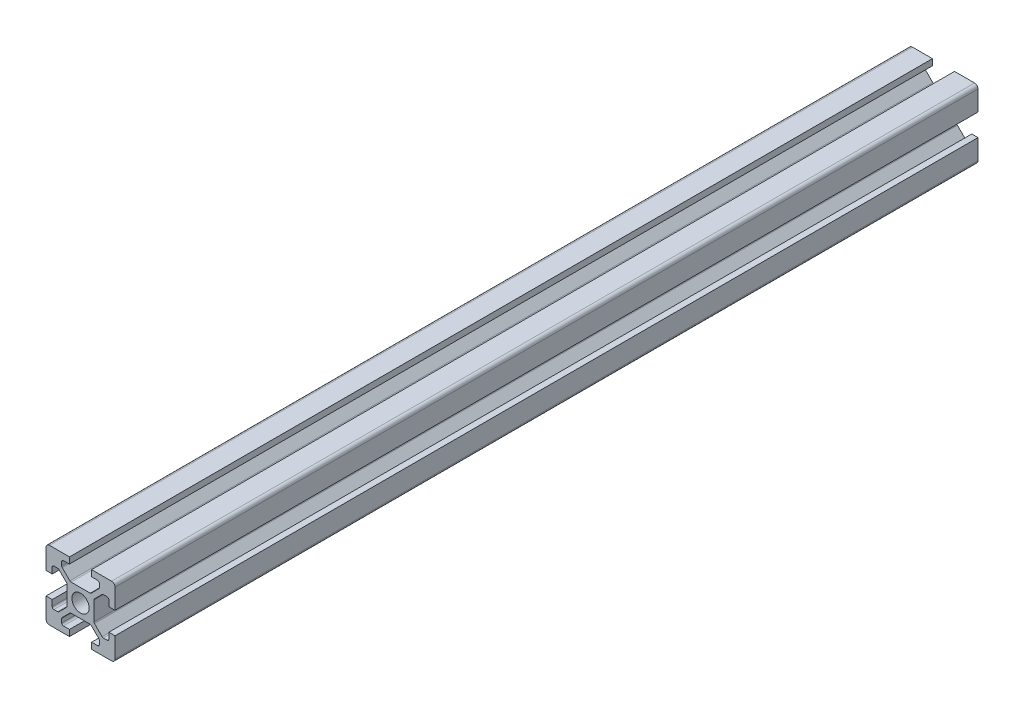
SolidWorks part; units mm, degrees
material "1060 Alloy"
ref_plane "Front Plane" through (0, 0, 0) normal (0, 0, 1) x (1, 0, 0)
ref_plane "Top Plane" through (0, 0, 0) normal (0, 1, 0) x (1, 0, 0)
ref_plane "Right Plane" through (0, 0, 0) normal (1, 0, 0) x (0, 0, -1)
sketch "Sketch1" plane through (0, 0, 0) normal (0, 0, 1) x (1, 0, 0)
  line L0 (20, 0) -> (-8.059, 28.059) construction
  line L1 (0, 0) -> (6.8, 0)
  line L2 (0, 0) -> (0, 6.8)
  line L3 (0, 20) -> (6.8, 20)
  line L4 (20, 0) -> (20, 6.8)
  line L5 (6.8, 20) -> (6.8, 18.2)
  line L6 (20, 20) -> (8.2322, 8.2322) construction
  line L7 (12.95, 6.1) -> (7.05, 6.1)
  line L8 (13.9, 7.05) -> (13.9, 12.95)
  line L9 (12.95, 13.9) -> (7.05, 13.9)
  line L10 (6.1, 7.05) -> (6.1, 12.95)
  line L11 (13.9, 6.1) -> (6.1, 13.9) construction
  line L12 (13.9, 13.9) -> (6.1, 6.1) construction
  line L13 (4.55, 16.4) -> (7.05, 13.9)
  line L14 (13.2, 18.2) -> (13.2, 20)
  line L15 (1.8, 6.8) -> (0, 6.8)
  line L16 (0, 13.2) -> (0, 20)
  line L17 (0, 13.2) -> (1.8, 13.2)
  line L18 (10, 10) -> (10, 13.9) construction
  line L19 (16.4, 4.55) -> (13.9, 7.05)
  line L20 (4.55, 16.4) -> (4.55, 18.2)
  line L21 (4.55, 18.2) -> (6.8, 18.2)
  line L22 (13.2, 18.2) -> (15.45, 18.2)
  line L23 (15.45, 18.2) -> (15.45, 16.4)
  line L24 (15.45, 16.4) -> (12.95, 13.9)
  line L25 (16.4, 4.55) -> (18.2, 4.55)
  line L26 (18.2, 4.55) -> (18.2, 6.8)
  line L27 (20, 6.8) -> (18.2, 6.8)
  line L28 (18.2, 13.2) -> (20, 13.2)
  line L29 (18.2, 13.2) -> (18.2, 15.45)
  line L30 (18.2, 15.45) -> (16.4, 15.45)
  line L31 (16.4, 15.45) -> (13.9, 12.95)
  line L32 (1.8, 4.55) -> (3.6, 4.55)
  line L33 (3.6, 15.45) -> (6.1, 12.95)
  line L34 (3.6, 15.45) -> (1.8, 15.45)
  line L35 (1.8, 15.45) -> (1.8, 13.2)
  line L36 (0, 13.2) -> (1.8, 13.2)
  line L37 (1.8, 6.8) -> (0, 6.8)
  line L38 (3.6, 4.55) -> (6.1, 7.05)
  line L39 (1.8, 6.8) -> (1.8, 4.55)
  line L40 (15.45, 3.6) -> (12.95, 6.1)
  line L41 (4.55, 3.6) -> (7.05, 6.1)
  line L42 (4.55, 1.8) -> (4.55, 3.6)
  line L43 (6.8, 1.8) -> (4.55, 1.8)
  line L44 (6.8, 1.8) -> (6.8, 0)
  line L45 (15.45, 3.6) -> (15.45, 1.8)
  line L46 (15.45, 1.8) -> (13.2, 1.8)
  line L47 (13.2, 0) -> (13.2, 1.8)
  line L48 (13.2, 20) -> (20, 20)
  line L49 (20, 13.2) -> (20, 20)
  line L50 (13.2, 0) -> (20, 0)
  line L51 (6.1, 6.1) -> (-5.5045, -5.5045) construction
  circle A0 centre (10, 10) radius 2.5
  point P25 (10, 16.4)
  point P39 (13.2, 19.1)
  point P46 (0.9, 6.8)
  dimension "D3" = 5
  dimension "D2" = 20
  dimension "D4" = 7.8
  dimension "D5" = 7.8
  dimension "D6" = 6.8
  dimension "D7" = 6.8
  dimension "D8" = 1.8
  dimension "D9" = 10.9
  dimension "D10" = 1.8
  dimension "D11" = 10.9
  dimension "D12" = 20
extrude "Boss-Extrude1" add sketch "Sketch1" along normal blind 250 contours L47 L50 L4 L27 L26 L25 L19 L8 L31 L30 L29 L28 L49 L48 L14 L22 L23 L24 L9 L13 L20 L21 L5 L3 L16 L17 L35 L34 L33 L10 L38 L32 L39 L15 L2 L1 L44 L43 L42 L41 L7 L40 L45 L46 A0
fillet "Fillet1" radius 1 4 edges at (20, 20, 125) (20, 0, 125) (0, 0, 125) (0, 20, 125)
fillet "Fillet2" radius 0.5 6 edges at (4.55, 18.2, 125) (4.55, 16.4, 125) (7.05, 13.9, 125) (15.45, 18.2, 125) (15.45, 16.4, 125) (12.95, 13.9, 125)
fillet "Fillet3" radius 0.5 6 edges at (18.2, 15.45, 125) (16.4, 15.45, 125) (13.9, 12.95, 125) (18.2, 4.55, 125) (13.9, 7.05, 125) (16.4, 4.55, 125)
fillet "Fillet4" radius 0.5 6 edges at (1.8, 15.45, 125) (3.6, 15.45, 125) (6.1, 12.95, 125) (3.6, 4.55, 125) (1.8, 4.55, 125) (6.1, 7.05, 125)
fillet "Fillet5" radius 0.5 6 edges at (7.05, 6.1, 125) (4.55, 3.6, 125) (4.55, 1.8, 125) (15.45, 1.8, 125) (15.45, 3.6, 125) (12.95, 6.1, 125)
